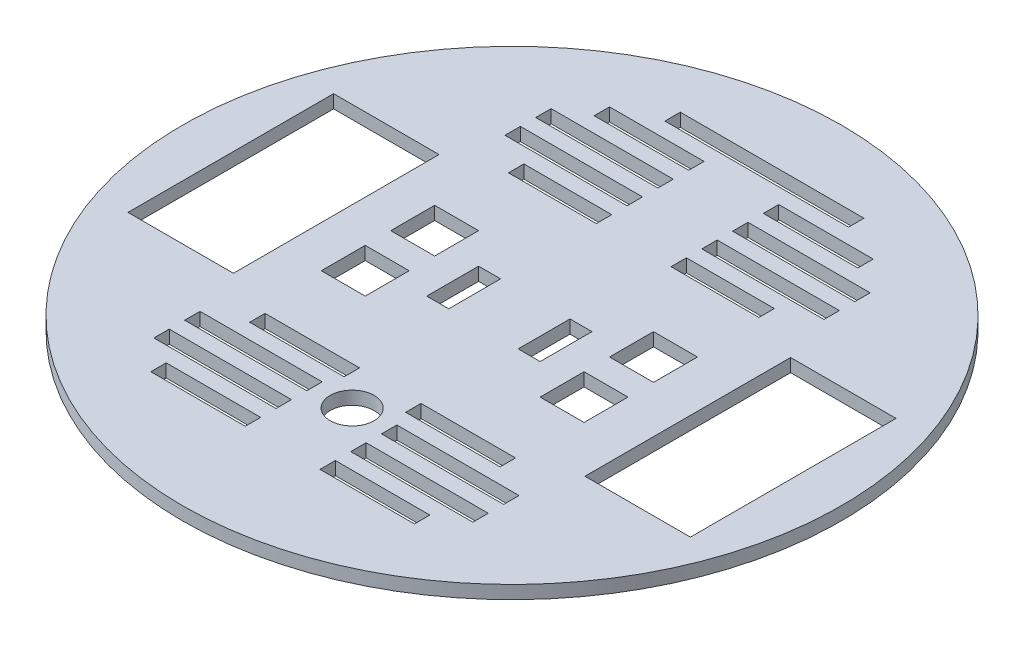
SolidWorks part; units mm, degrees
ref_plane "Alzado" through (0, 0, 0) normal (0, 0, 1) x (1, 0, 0)
ref_plane "Planta" through (0, 0, 0) normal (0, 1, 0) x (1, 0, 0)
ref_plane "Vista lateral" through (0, 0, 0) normal (1, 0, 0) x (0, 0, -1)
ref_plane "Plano1" through (0, 0, 0) normal (0, -1, 0) x (1, 0, 0)
sketch "Croquis1" plane through (0, 0, 0) normal (0, -1, 0) x (1, 0, 0)
  line L0 (37.3854, 26.1768) -> (61.3854, 26.1768)
  line L1 (61.3854, 26.1768) -> (61.3854, -20.6232)
  line L2 (61.3854, -20.6232) -> (37.3854, -20.6232)
  line L3 (37.3854, -20.6232) -> (37.3854, 26.1768)
  line L4 (-42.6146, 26.1768) -> (-42.6146, -20.6232)
  line L5 (-42.6146, -20.6232) -> (-66.6146, -20.6232)
  line L6 (-66.6146, -20.6232) -> (-66.6146, 26.1768)
  line L7 (-66.6146, 26.1768) -> (-42.6146, 26.1768)
  line L8 (18.2854, -56.4232) -> (-23.5146, -56.4232)
  line L9 (-23.5146, -56.4232) -> (-23.5146, -52.9232)
  line L10 (-23.5146, -52.9232) -> (18.2854, -52.9232)
  line L11 (18.2854, -52.9232) -> (18.2854, -56.4232)
  line L12 (26.6854, 5.6768) -> (16.6854, 5.6768)
  line L13 (16.6854, 5.6768) -> (16.6854, 15.6768)
  line L14 (16.6854, 15.6768) -> (26.6854, 15.6768)
  line L15 (26.6854, 15.6768) -> (26.6854, 5.6768)
  line L16 (16.6854, -0.1232) -> (26.6854, -0.1232)
  line L17 (26.6854, -0.1232) -> (26.6854, -10.1232)
  line L18 (26.6854, -10.1232) -> (16.6854, -10.1232)
  line L19 (16.6854, -10.1232) -> (16.6854, -0.1232)
  line L20 (-23.1146, 15.6768) -> (-23.1146, 5.6768)
  line L21 (-23.1146, 5.6768) -> (-33.1146, 5.6768)
  line L22 (-33.1146, 5.6768) -> (-33.1146, 15.6768)
  line L23 (-33.1146, 15.6768) -> (-23.1146, 15.6768)
  line L24 (-33.1146, -10.1232) -> (-33.1146, -0.1232)
  line L25 (-33.1146, -0.1232) -> (-23.1146, -0.1232)
  line L26 (-23.1146, -0.1232) -> (-23.1146, -10.1232)
  line L27 (-23.1146, -10.1232) -> (-33.1146, -10.1232)
  line L28 (33.6854, 44.4768) -> (5.8854, 44.4768)
  line L29 (5.8854, 44.4768) -> (5.8854, 47.9768)
  line L30 (5.8854, 47.9768) -> (33.6854, 47.9768)
  line L31 (33.6854, 47.9768) -> (33.6854, 44.4768)
  line L32 (5.8854, 40.9768) -> (33.6854, 40.9768)
  line L33 (33.6854, 40.9768) -> (33.6854, 37.4768)
  line L34 (33.6854, 37.4768) -> (5.8854, 37.4768)
  line L35 (5.8854, 37.4768) -> (5.8854, 40.9768)
  line L36 (-11.1146, 47.9768) -> (-11.1146, 44.4768)
  line L37 (-11.1146, 44.4768) -> (-38.9146, 44.4768)
  line L38 (-38.9146, 44.4768) -> (-38.9146, 47.9768)
  line L39 (-38.9146, 47.9768) -> (-11.1146, 47.9768)
  line L40 (-38.9146, 40.9768) -> (-11.1146, 40.9768)
  line L41 (-11.1146, 40.9768) -> (-11.1146, 37.4768)
  line L42 (-11.1146, 37.4768) -> (-38.9146, 37.4768)
  line L43 (-38.9146, 37.4768) -> (-38.9146, 40.9768)
  line L44 (33.6854, -31.9232) -> (33.6854, -35.4232)
  line L45 (33.6854, -35.4232) -> (5.8854, -35.4232)
  line L46 (5.8854, -35.4232) -> (5.8854, -31.9232)
  line L47 (5.8854, -31.9232) -> (33.6854, -31.9232)
  line L48 (5.8854, -42.4232) -> (5.8854, -38.9232)
  line L49 (5.8854, -38.9232) -> (33.6854, -38.9232)
  line L50 (33.6854, -38.9232) -> (33.6854, -42.4232)
  line L51 (33.6854, -42.4232) -> (5.8854, -42.4232)
  line L52 (-38.9146, -31.9232) -> (-11.1146, -31.9232)
  line L53 (-11.1146, -31.9232) -> (-11.1146, -35.4232)
  line L54 (-11.1146, -35.4232) -> (-38.9146, -35.4232)
  line L55 (-38.9146, -35.4232) -> (-38.9146, -31.9232)
  line L56 (-38.9146, -38.9232) -> (-11.1146, -38.9232)
  line L57 (-11.1146, -38.9232) -> (-11.1146, -42.4232)
  line L58 (-11.1146, -42.4232) -> (-38.9146, -42.4232)
  line L59 (-38.9146, -42.4232) -> (-38.9146, -38.9232)
  line L60 (-9.6146, 30.4768) -> (-31.1146, 30.4768)
  line L61 (-31.1146, 30.4768) -> (-31.1146, 33.9768)
  line L62 (-31.1146, 33.9768) -> (-9.6146, 33.9768)
  line L63 (-9.6146, 33.9768) -> (-9.6146, 30.4768)
  line L64 (27.3854, 51.4768) -> (5.8854, 51.4768)
  line L65 (5.8854, 51.4768) -> (5.8854, 54.9768)
  line L66 (5.8854, 54.9768) -> (27.3854, 54.9768)
  line L67 (27.3854, 54.9768) -> (27.3854, 51.4768)
  line L68 (25.8854, 33.9768) -> (25.8854, 30.4768)
  line L69 (25.8854, 30.4768) -> (4.3854, 30.4768)
  line L70 (4.3854, 30.4768) -> (4.3854, 33.9768)
  line L71 (4.3854, 33.9768) -> (25.8854, 33.9768)
  line L72 (-11.1146, 54.9768) -> (-11.1146, 51.4768)
  line L73 (-11.1146, 51.4768) -> (-32.6146, 51.4768)
  line L74 (-32.6146, 51.4768) -> (-32.6146, 54.9768)
  line L75 (-32.6146, 54.9768) -> (-11.1146, 54.9768)
  line L76 (5.8854, -49.4232) -> (5.8854, -45.9232)
  line L77 (5.8854, -45.9232) -> (27.3854, -45.9232)
  line L78 (27.3854, -45.9232) -> (27.3854, -49.4232)
  line L79 (27.3854, -49.4232) -> (5.8854, -49.4232)
  line L80 (-32.6146, -49.4232) -> (-32.6146, -45.9232)
  line L81 (-32.6146, -45.9232) -> (-11.1146, -45.9232)
  line L82 (-11.1146, -45.9232) -> (-11.1146, -49.4232)
  line L83 (-11.1146, -49.4232) -> (-32.6146, -49.4232)
  line L84 (25.8854, -28.4232) -> (5.8854, -28.4232)
  line L85 (5.8854, -28.4232) -> (5.8854, -24.9232)
  line L86 (5.8854, -24.9232) -> (25.8854, -24.9232)
  line L87 (25.8854, -24.9232) -> (25.8854, -28.4232)
  line L88 (-11.1146, -28.4232) -> (-31.1146, -28.4232)
  line L89 (-31.1146, -28.4232) -> (-31.1146, -24.9232)
  line L90 (-31.1146, -24.9232) -> (-11.1146, -24.9232)
  line L91 (-11.1146, -24.9232) -> (-11.1146, -28.4232)
  line L92 (9.6854, -3.1232) -> (4.6854, -3.1232)
  line L93 (4.6854, -3.1232) -> (4.6854, 8.6768)
  line L94 (4.6854, 8.6768) -> (9.6854, 8.6768)
  line L95 (9.6854, 8.6768) -> (9.6854, -3.1232)
  line L96 (-16.1146, -3.1232) -> (-16.1146, 8.6768)
  line L97 (-16.1146, 8.6768) -> (-11.1146, 8.6768)
  line L98 (-11.1146, 8.6768) -> (-11.1146, -3.1232)
  line L99 (-11.1146, -3.1232) -> (-16.1146, -3.1232)
  circle A0 centre (-2.5464, 39.2268) radius 5
  circle A1 centre (-2.6146, 2.7768) radius 75
extrude "Saliente-Extruir1" add sketch "Croquis1" against normal blind 3
